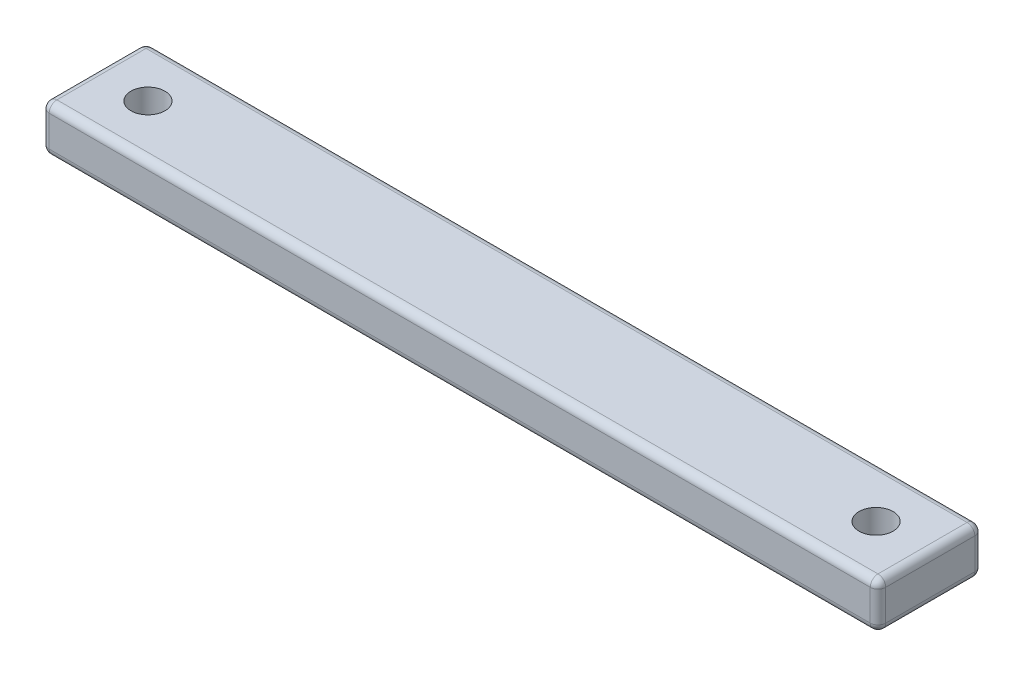
SolidWorks part; units mm, degrees
ref_plane "Front Plane" through (0, 0, 0) normal (0, 0, 1) x (1, 0, 0)
ref_plane "Top Plane" through (0, 0, 0) normal (0, 1, 0) x (1, 0, 0)
ref_plane "Right Plane" through (0, 0, 0) normal (1, 0, 0) x (0, 0, -1)
sketch "Sketch1" plane through (0, 0, 0) normal (0, 1, 0) x (1, 0, 0)
  line L0 (-27, 0) -> (-20, 0) construction
  line L1 (-27, -3.375) -> (27, -3.375)
  line L2 (-27, -3.375) -> (-27, 3.375)
  line L3 (-27, 3.375) -> (27, 3.375)
  line L4 (27, -3.375) -> (27, 3.375)
  line L5 (-27, -3.375) -> (27, 3.375) construction
  line L6 (-27, 3.375) -> (27, -3.375) construction
  line L7 (27, 0) -> (20, 0) construction
  circle A1 centre (-23.5, 0) radius 1.1
  circle A2 centre (23.5, 0) radius 1.1
  point P0 (0, 0)
  dimension "D1" = 6.75
  dimension "D5" = 2.2
  dimension "D6" = 2.2
  dimension "D2" = 54
  dimension "D3" = 7
  dimension "D4" = 7
extrude "Boss-Extrude1" add sketch "Sketch1" along normal blind 3
fillet "Fillet1" radius 0.5 12 edges at (27, 3, 0) (27, 0, 0) (27, 1.5, -3.375) (0, 3, -3.375) (0, 0, -3.375) (-27, 1.5, -3.375) (-27, 3, 0) (-27, 0, 0) (-27, 1.5, 3.375) (0, 3, 3.375) (27, 1.5, 3.375) (0, 0, 3.375)
